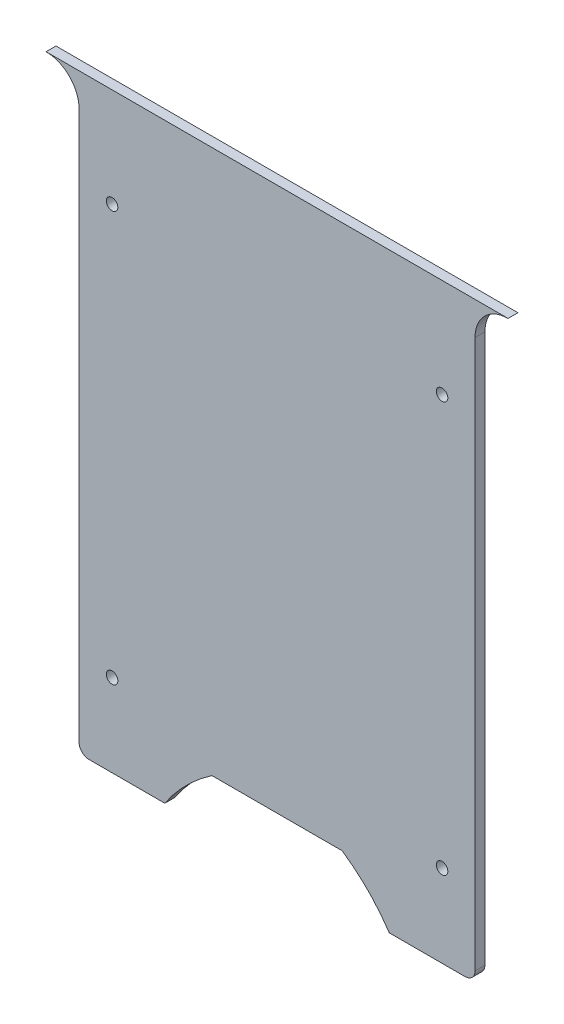
SolidWorks part; units mm, degrees
ref_plane "Front Plane" through (0, 0, 0) normal (0, 0, 1) x (1, 0, 0)
ref_plane "Top Plane" through (0, 0, 0) normal (0, 1, 0) x (1, 0, 0)
ref_plane "Right Plane" through (0, 0, 0) normal (1, 0, 0) x (0, 0, -1)
sketch "Sketch1" plane through (0, 0, 0) normal (0, 0, 1) x (1, 0, 0)
  line L14 (-70, 219) -> (70, 219)
  line L31 (60, 42.7463) -> (60, 209)
  line L32 (34.0107, 39.7463) -> (57, 39.7463)
  line L33 (-19.7266, 54.15) -> (19.7266, 54.15)
  line L34 (-57, 39.7463) -> (-34.0107, 39.7463)
  line L35 (-60, 209) -> (-60, 42.7463)
  circle A2 centre (50, 64.7463) radius 1.75
  circle A8 centre (50, 189) radius 1.75
  circle A14 centre (-50, 189) radius 1.75
  circle A16 centre (-50, 64.7463) radius 1.75
  arc A32 (70, 219) -> (60, 209) centre (70, 209) ccw
  arc A33 (57, 39.7463) -> (60, 42.7463) centre (57, 42.7463) ccw
  arc A34 (-60, 42.7463) -> (-57, 39.7463) centre (-57, 42.7463) ccw
  arc A35 (-60, 209) -> (-70, 219) centre (-70, 209) ccw
  parabola Q4 (19.7266, 54.15) -> (34.0107, 39.7463) focus (9.6843, 28.5899) apex (28.837, 46.3163)
  parabola Q5 (-34.0107, 39.7463) -> (-19.7266, 54.15) focus (-9.6843, 28.5899) apex (-28.837, 46.3163)
extrude "Boss-Extrude1" add sketch "Sketch1" along normal blind 3
